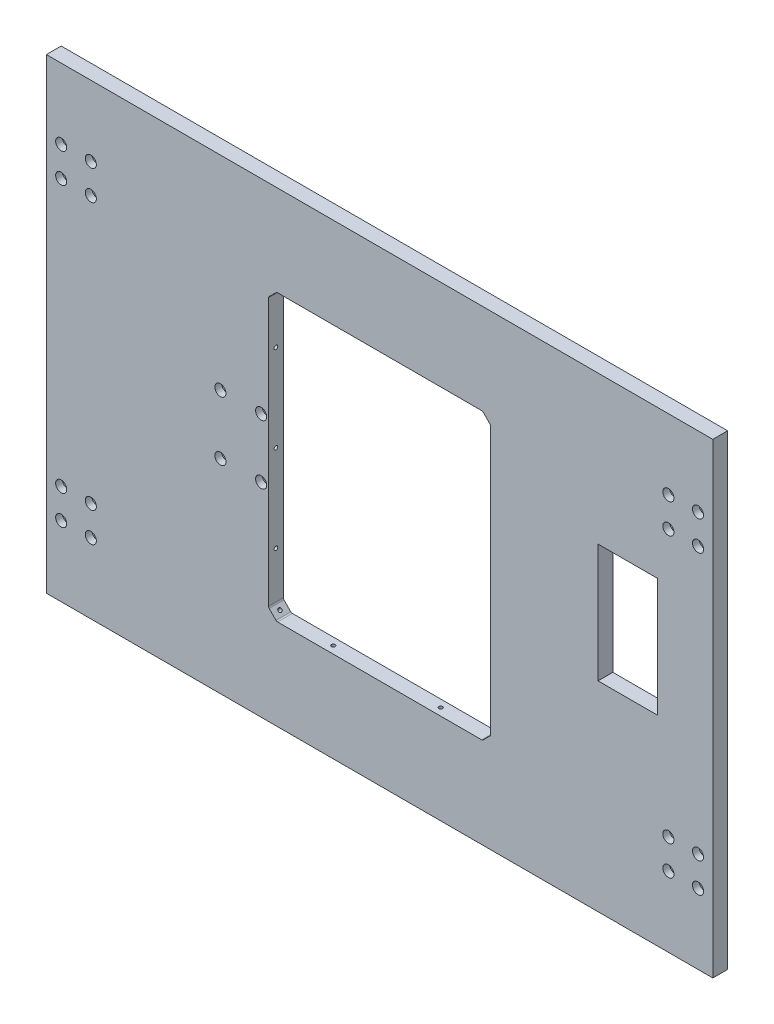
SolidWorks part; units mm, degrees
material "6061 Alloy"
ref_plane "Front Plane" through (0, 0, 0) normal (0, 0, 1) x (1, 0, 0)
ref_plane "Top Plane" through (0, 0, 0) normal (0, 1, 0) x (1, 0, 0)
ref_plane "Right Plane" through (0, 0, 0) normal (1, 0, 0) x (0, 0, -1)
sketch "Sketch1" plane through (0, 0, 0) normal (0, 0, 1) x (1, 0, 0)
  line L1 (450, -315) -> (-450, -315)
  line L2 (450, -315) -> (450, 315)
  line L3 (450, 315) -> (-450, 315)
  line L4 (-450, -315) -> (-450, 315)
  line L5 (450, -315) -> (-450, 315) construction
  line L6 (450, 315) -> (-450, -315) construction
  point P0 (0, 0)
  dimension "D1" = 630
  dimension "D2" = 900
extrude "Boss-Extrude1" add sketch "Sketch1" along normal blind 20
sketch "Sketch2" plane through (0, 0, 20) normal (0, 0, 1) x (1, 0, 0)
  line L1 (150, -192.5) -> (-150, -192.5)
  line L2 (150, -192.5) -> (150, 192.5)
  line L3 (150, 192.5) -> (-150, 192.5)
  line L4 (-150, -192.5) -> (-150, 192.5)
  line L5 (150, -192.5) -> (-150, 192.5) construction
  line L6 (150, 192.5) -> (-150, -192.5) construction
  point P0 (0, 0)
  dimension "D1" = 385
  dimension "D2" = 300
extrude "Cut-Extrude1" cut sketch "Sketch2" against normal through all
chamfer "Chamfer1" distance 11 angle 45 4 edges at (-150, -192.5, 10) (150, -192.5, 10) (150, 192.5, 10) (-150, 192.5, 10)
hole_wizard "M6 Tapped Hole1" positions "Sketch3" profile "Sketch4" tap size "M6" standard "GB"
sketch "Sketch3" plane through (-165.75, 165.75, 0) normal (0.7071, -0.7071, 0) x (0, 0, -1)
  line L0 (-20, 30.052) -> (0, 30.052) construction
  line L1 (-20, 22.2739) -> (-20, 37.8302) construction
  line L2 (0, 37.8302) -> (0, 22.2739) construction
  point P0 (-10, 30.052)
sketch "Sketch4" plane through (-144.5, 187, 10) normal (0, 0, 1) x (0.7071, 0.7071, 0)
  line L0 (0, 0) -> (0, 31.5022)
  line L1 (0, 31.5022) -> (2.5, 30)
  line L2 (2.5, 30) -> (2.5, 0)
  line L5 (2.5, 0) -> (0, 0)
  line L10 (0, 31.5022) -> (-2.5, 30) construction
  line L11 (0, -6.35) -> (0, 107.95) construction
  dimension "Tap Drill Dia." = 5
  dimension "Tap Drill Depth" = 30
  dimension "Drill Angle" = 118
fillet "Fillet1" radius 3 8 edges at (-139, -192.5, 10) (139, -192.5, 10) (150, -181.5, 10) (150, 181.5, 10) (139, 192.5, 10) (-139, 192.5, 10) (-150, 181.5, 10) (-150, -181.5, 10)
hole_wizard "M6 Tapped Hole2" positions "Sketch5" profile "Sketch6" tap size "M6" standard "GB"
sketch "Sketch5" plane through (-150, 0, 0) normal (1, 0, 0) x (0, 0, -1)
  line L2 (-20, 117.5) -> (0, 117.5) construction
  line L3 (-20, 180.2574) -> (-20, -180.2574) construction
  line L4 (0, 180.2574) -> (0, -180.2574) construction
  line L6 (-20, 0) -> (0, 0) construction
  point P0 (-10, 0)
  point P2 (-10, 117.5)
  dimension "D1" = 117.5
sketch "Sketch6" plane through (-150, 0, 10) normal (0, 1, 0) x (0, 0, -1)
  line L0 (0, 0) -> (0, 31.5022)
  line L1 (0, 31.5022) -> (2.5, 30)
  line L2 (2.5, 30) -> (2.5, 0)
  line L5 (2.5, 0) -> (0, 0)
  line L10 (0, 31.5022) -> (-2.5, 30) construction
  line L11 (0, -6.35) -> (0, 107.95) construction
  dimension "Tap Drill Dia." = 5
  dimension "Tap Drill Depth" = 30
  dimension "Drill Angle" = 118
hole_wizard "M6 Tapped Hole3" positions "Sketch7" profile "Sketch8" tap size "M6" standard "GB"
sketch "Sketch7" plane through (0, 192.5, 0) normal (0, -1, 0) x (-1, 0, 0)
  line L0 (-137.7574, -20) -> (137.7574, -20) construction
  line L1 (72.5, -20) -> (72.5, 0) construction
  line L2 (-137.7574, 0) -> (137.7574, 0) construction
  point P0 (72.5, -10)
  dimension "D1" = 72.5
sketch "Sketch8" plane through (-72.5, 192.5, 10) normal (1, 0, 0) x (0, 0, -1)
  line L0 (0, 0) -> (0, 31.5022)
  line L1 (0, 31.5022) -> (2.5, 30)
  line L2 (2.5, 30) -> (2.5, 0)
  line L5 (2.5, 0) -> (0, 0)
  line L10 (0, 31.5022) -> (-2.5, 30) construction
  line L11 (0, -6.35) -> (0, 107.95) construction
  dimension "Tap Drill Dia." = 5
  dimension "Tap Drill Depth" = 30
  dimension "Drill Angle" = 118
mirror "Mirror1" about plane through (0, 0, 0) normal (1, 0, 0) of "M6 Tapped Hole1", "M6 Tapped Hole3", "M6 Tapped Hole2" second plane through (0, 0, 0) second plane normal (0, 1, 0)
sketch "Sketch9" plane through (0, 0, 0) normal (0, 0, -1) x (-1, 0, 0)
  line L5 (150, 180.2574) -> (150, -180.2574) construction
  line L6 (230, 45) -> (150, 45)
  line L7 (230, 45) -> (230, -45)
  line L8 (230, -45) -> (150, -45)
  line L9 (150, 45) -> (150, -45)
  line L10 (230, 45) -> (150, -45) construction
  line L11 (230, -45) -> (150, 45) construction
  point P0 (190, 0)
  dimension "D1" = 80
  dimension "D2" = 90
extrude "Cut-Extrude2" [suppressed] cut sketch "Sketch9" against normal blind 5
chamfer "Chamfer2" [suppressed] distance 10 angle 45
fillet "Fillet2" [suppressed] radius 3
hole_wizard "CBORE for M8 Hexagon socket head cap screws1" positions "Sketch10" profile "Sketch11" counterbore size "M8" standard "GB" end condition through all
sketch "Sketch10" plane through (0, 0, 20) normal (0, 0, 1) x (1, 0, 0)
  line L0 (11, 0) -> (-11, 0) construction
  point P0 (-430, 220)
  point P3 (-390, 220)
  point P6 (-430, 180)
  point P8 (-390, 180)
  point P11 (-215.0019, 40)
  point P14 (-160.0019, 40)
  point P22 (390, 220)
  point P25 (430, 220)
  point P28 (390, 180)
  point P31 (430, 180)
  point P52 (430, -180)
  point P53 (390, -180)
  point P54 (430, -220)
  point P55 (390, -220)
  point P56 (-160.0019, -40)
  point P57 (-215.0019, -40)
  point P58 (-390, -180)
  point P59 (-430, -180)
  point P60 (-390, -220)
  point P61 (-430, -220)
  dimension "D1" = 390
  dimension "D2" = 180
  dimension "D3" = 40
  dimension "D4" = 40
  dimension "D5" = 40
  dimension "D6" = 390
  dimension "D7" = 55
  dimension "D8" = 160.0019
  dimension "D9" = 40
sketch "Sketch11" plane through (-430, 220, 20) normal (1, 0, 0) x (0, -1, 0)
  line L0 (0, 0) -> (0, 20)
  line L1 (0, 20) -> (4.2, 20)
  line L3 (4.2, 20) -> (4.2, 9)
  line L4 (4.2, 9) -> (7.5, 9)
  line L5 (7.5, 9) -> (7.5, 0)
  line L7 (7.5, 0) -> (0, 0)
  line L11 (0, -6.35) -> (0, 107.95) construction
  dimension "Thru Hole Dia." = 8.4
  dimension "Thru Hole Depth" = 20
  dimension "C'Bore Dia." = 15
  dimension "C'Bore Depth" = 9
sketch "Sketch12" [suppressed] plane through (0, 0, 5) normal (0, 0, -1) x (-1, 0, 0)
  line L5 (150, -2.5) -> (180, -2.5) construction
  line L6 (150, 2.5) -> (181.5022, 2.5)
  line L7 (150, 2.5) -> (150, -2.5)
  line L8 (150, -2.5) -> (181.5022, -2.5)
  line L9 (181.5022, 2.5) -> (181.5022, -2.5)
extrude "Boss-Extrude2" [suppressed] add sketch "Sketch12" against normal up to next
sketch "Sketch13" plane through (0, 0, 20) normal (0, 0, 1) x (1, 0, 0)
  line L0 (335, -315) -> (335, 315) construction
  line L1 (375, -45) -> (295, -45)
  line L2 (375, -45) -> (375, 115)
  line L3 (375, 115) -> (295, 115)
  line L4 (295, -45) -> (295, 115)
  line L5 (375, -45) -> (295, 115) construction
  line L6 (375, 115) -> (295, -45) construction
  line L8 (-450, -315) -> (450, -315) construction
  line L9 (450, 315) -> (-450, 315) construction
  point P0 (335, 35)
  point P17 (335, 0)
  dimension "D1" = 335
  dimension "D2" = 80
  dimension "D3" = 160
  dimension "D4" = 35
extrude "Cut-Extrude3" cut sketch "Sketch13" against normal through all
